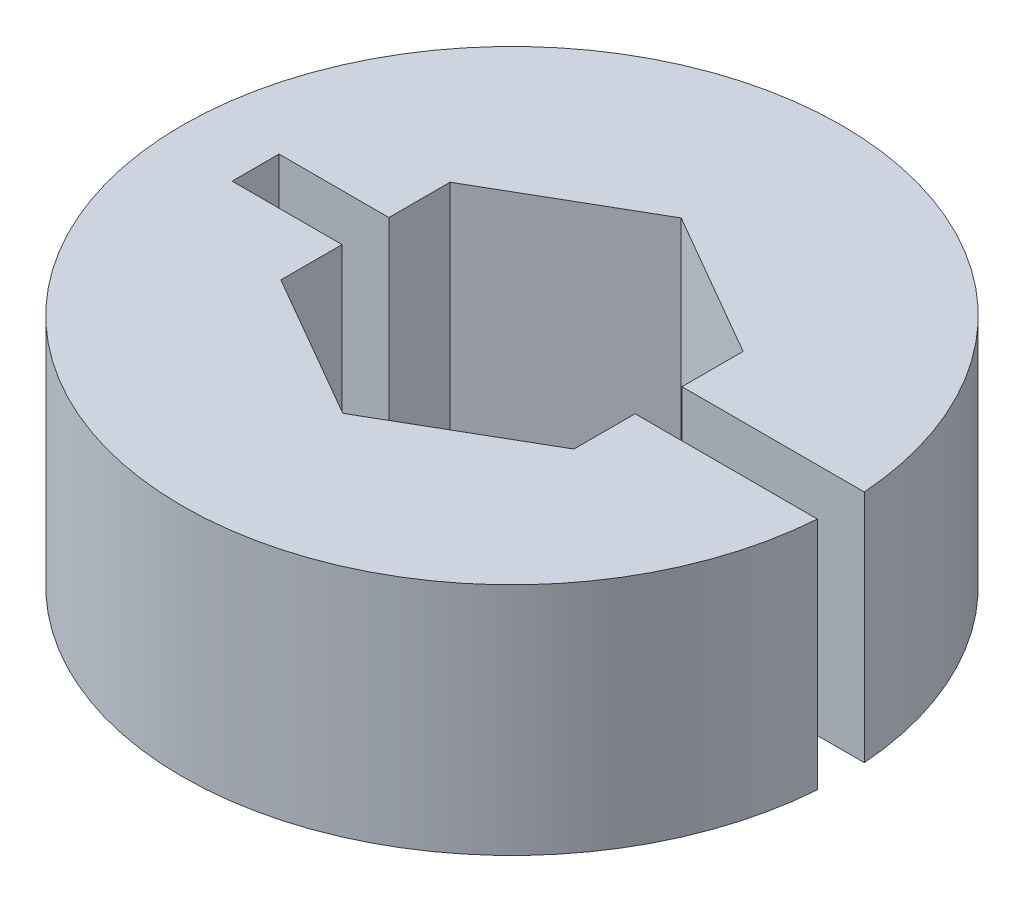
SolidWorks part; units mm, degrees
ref_plane "Front Plane" through (0, 0, 0) normal (0, 0, 1) x (1, 0, 0)
ref_plane "Top Plane" through (0, 0, 0) normal (0, 1, 0) x (1, 0, 0)
ref_plane "Right Plane" through (0, 0, 0) normal (1, 0, 0) x (0, 0, -1)
sketch "Sketch1" plane through (0, 0, 0) normal (0, 1, 0) x (1, 0, 0)
  circle A0 centre (0, 0) radius 14.2875
  dimension "D1" = 28.575
extrude "Boss-Extrude1" add sketch "Sketch1" along normal blind 10.16
sketch "Sketch2" plane through (0, 10.16, 0) normal (0, 1, 0) x (1, 0, 0)
  line L1 (0, 7.3323) -> (-6.35, 3.6662)
  line L2 (-6.35, 3.6662) -> (-6.35, -3.6662)
  line L3 (-6.35, -3.6662) -> (0, -7.3323)
  line L4 (0, -7.3323) -> (6.35, -3.6662)
  line L5 (6.35, -3.6662) -> (6.35, 3.6662)
  line L6 (6.35, 3.6662) -> (0, 7.3323)
  circle A0 centre (0, 0) radius 6.35 construction
  point P1 (0, 0)
  dimension "D1" = 12.7
extrude "Cut-Extrude1" cut sketch "Sketch2" against normal through all
sketch "Sketch3" plane through (0, 10.16, 0) normal (0, 1, 0) x (1, 0, 0)
  line L1 (-11.1125, -1.016) -> (14.2875, -1.016)
  line L2 (-11.1125, -1.016) -> (-11.1125, 1.016)
  line L3 (-11.1125, 1.016) -> (14.2875, 1.016)
  line L4 (14.2875, -1.016) -> (14.2875, 1.016)
  line L5 (-11.1125, -1.016) -> (14.2875, 1.016) construction
  line L6 (-11.1125, 1.016) -> (14.2875, -1.016) construction
  circle A0 centre (0, 0) radius 14.2875 construction
  point P0 (1.5875, 0)
  point P5 (0.5567, 0)
  point P6 (0.4616, 0)
  point P7 (0.2318, 0)
  point P9 (0, 0)
  point P10 (0, 0)
  point P11 (0, 0)
  point P12 (3.0738, 0)
  point P13 (-4.012, 0)
  point P14 (4.7366, 0)
  point P15 (3.0738, 0)
  dimension "D1" = 2.032
  dimension "D2" = 25.4
extrude "Cut-Extrude2" cut sketch "Sketch3" against normal through all contours L3 L4 L1 L2
